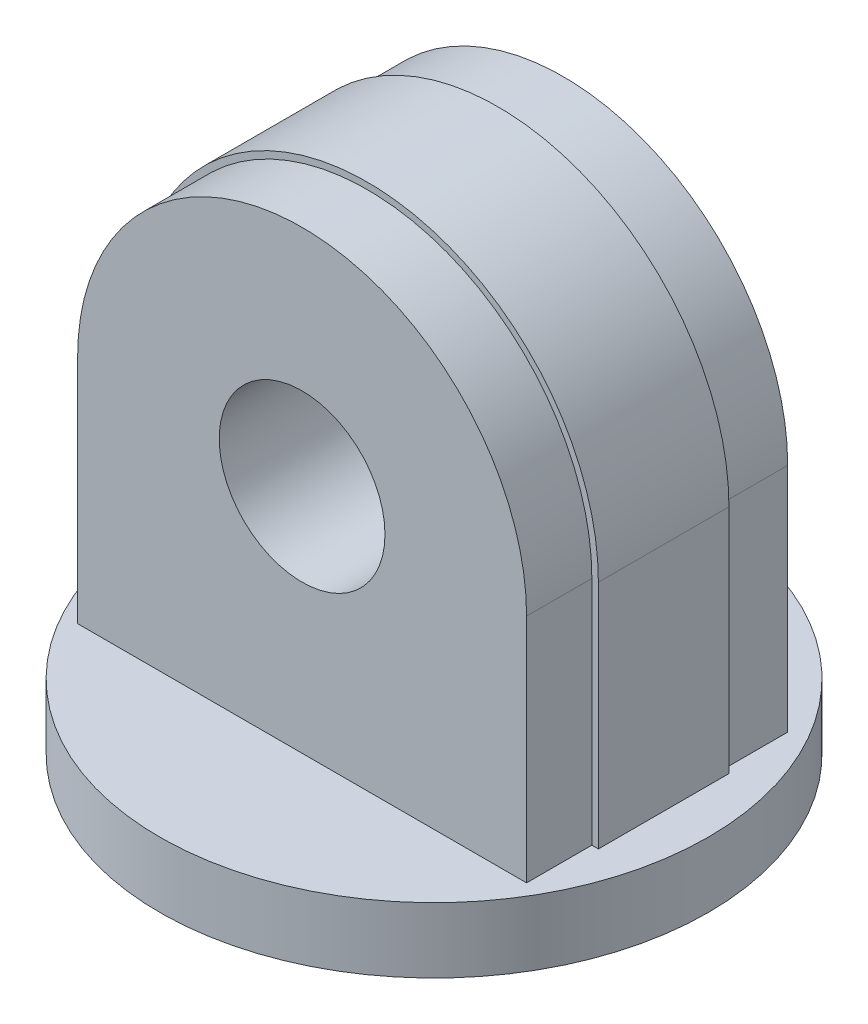
SolidWorks part; units mm, degrees
ref_plane "Front Plane" through (0, 0, 0) normal (0, 0, 1) x (1, 0, 0)
ref_plane "Top Plane" through (0, 0, 0) normal (0, 1, 0) x (1, 0, 0)
ref_plane "Right Plane" through (0, 0, 0) normal (1, 0, 0) x (0, 0, -1)
sketch "Sketch3" plane through (0, 0, 0) normal (0, 0, 1) x (1, 0, 0)
  line L0 (17.9777, -9.6973) -> (0, -9.6973)
  line L1 (0, -9.6973) -> (0, -0.7085)
  line L2 (17.9777, -0.7085) -> (17.9777, -9.6973)
  arc A1 (0, -0.7085) -> (17.9777, -0.7085) centre (8.9889, -0.7085) cw
extrude "Extrude1" add sketch "Sketch3" along normal mid plane 10.16
sketch "Sketch4" plane through (0, -9.6973, 0) normal (0, -1, 0) x (1, 0, 0)
  line L0 (0.1094, 5.08) -> (17.9777, -5.08) construction
  line L1 (0, 5.08) -> (17.9777, 5.08) construction
  circle A0 centre (9.0436, 0) radius 10.6746
extrude "Extrude2" add sketch "Sketch4" along normal blind 2.54
sketch "Sketch5" plane through (0, -12.2373, 0) normal (0, -1, 0) x (1, 0, 0)
  point P0 (9.0436, 0)
sketch "Sketch6" plane through (0, 0, 5.08) normal (0, 0, 1) x (1, 0, 0)
  circle A0 centre (8.9889, -0.7085) radius 3.225
  arc A1 (17.9777, -0.7085) -> (0, -0.7085) centre (8.9889, -0.7085) ccw construction
  dimension "D1" = 6.45
extrude "Cut-Extrude1" cut sketch "Sketch6" against normal through all
sketch "Sketch8" plane through (0, 0, 5.08) normal (0, 0, 1) x (1, 0, 0)
  line L0 (0.254, -9.6973) -> (0, -9.6973)
  line L1 (17.7237, -9.6973) -> (17.9777, -9.6973)
  line L2 (0, -0.7085) -> (0, -9.6973) construction
  line L3 (17.9777, -9.6973) -> (17.9777, -0.7085) construction
  line L4 (0.254, -0.7085) -> (0.254, -9.6973)
  line L5 (17.7237, -9.6973) -> (17.7237, -0.7085)
  line L6 (0.254, -0.7085) -> (0.254, -9.6973)
  line L7 (17.7237, -9.6973) -> (17.7237, -0.7085)
  line L8 (0, -0.7085) -> (0, -9.6973)
  line L9 (17.9777, -9.6973) -> (17.9777, -0.7085)
  arc A0 (17.9777, -0.7085) -> (0, -0.7085) centre (8.9889, -0.7085) ccw construction
  arc A1 (17.9777, -0.7085) -> (0, -0.7085) centre (8.9889, -0.7085) ccw
  arc A2 (17.7237, -0.7085) -> (0.254, -0.7085) centre (8.9889, -0.7085) ccw
  arc A3 (17.7237, -0.7085) -> (0.254, -0.7085) centre (8.9889, -0.7085) ccw
  dimension "D1" = 0.254
extrude "Extrude3" cut sketch "Sketch8" against normal blind 2.54
mirror "Mirror1" about plane through (0, 0, 0) normal (0, 0, 1) of "Extrude3"
